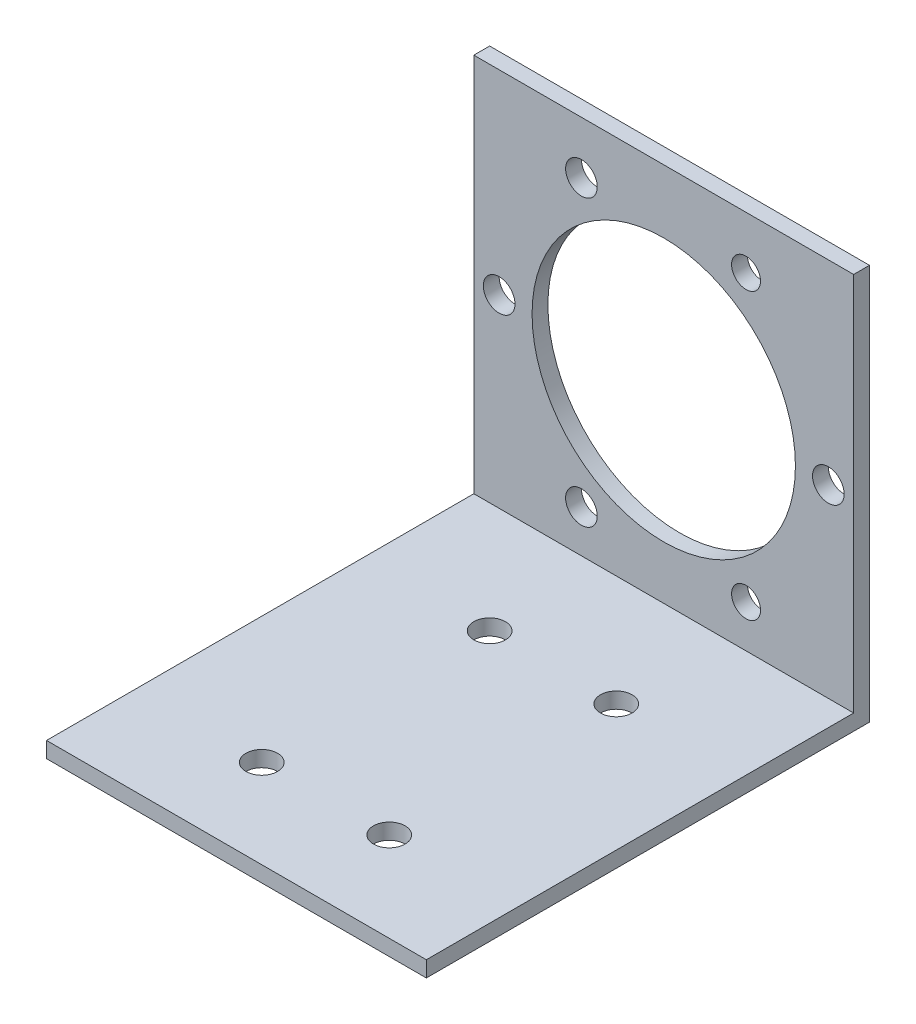
SolidWorks part; units mm, degrees
ref_plane "Front Plane" through (0, 0, 0) normal (0, 0, 1) x (1, 0, 0)
ref_plane "Top Plane" through (0, 0, 0) normal (0, 1, 0) x (1, 0, 0)
ref_plane "Right Plane" through (0, 0, 0) normal (1, 0, 0) x (0, 0, -1)
sketch "Sketch1" plane through (0, 0, 0) normal (0, 0, 1) x (1, 0, 0)
  line L1 (0, 0) -> (38.1, 0)
  line L2 (0, 0) -> (0, 1.5875)
  line L3 (0, 1.5875) -> (38.1, 1.5875)
  line L4 (38.1, 0) -> (38.1, 1.5875)
  dimension "D1" = 38.1
  dimension "D2" = 1.5875
extrude "Boss-Extrude1" add sketch "Sketch1" along normal blind 44.45
sketch "Sketch2" plane through (0, 1.5875, 0) normal (0, 1, 0) x (1, 0, 0)
  line L0 (12.7, -44.45) -> (12.7, 0) construction
  line L1 (38.1, -44.45) -> (0, -44.45) construction
  line L2 (38.1, 0) -> (0, 0) construction
  line L3 (25.4, 0) -> (25.4, -44.45) construction
  line L4 (38.1, -44.45) -> (38.1, 0) construction
  line L5 (0, 0) -> (38.1, 0)
  line L6 (0, 0) -> (0, -1.5875)
  line L7 (0, -1.5875) -> (38.1, -1.5875)
  line L8 (38.1, 0) -> (38.1, -1.5875)
  line L10 (0, -44.45) -> (0, 0) construction
  circle A0 centre (12.7, -12.7) radius 1.5875 construction
  circle A2 centre (12.7, -35.56) radius 1.5875 construction
  circle A3 centre (25.4, -35.4699) radius 1.5875 construction
  circle A5 centre (25.4, -12.7) radius 1.5875 construction
  dimension "D3" = 3.175
  dimension "D6" = 3.175
  dimension "D9" = 3.175
  dimension "D10" = 3.175
  dimension "D4" = 12.7
  dimension "D5" = 12.7
  dimension "D8" = 8.9801
  dimension "D11" = 8.89
  dimension "D12" = 1.5875
  dimension "D13" = 12.7
  dimension "D14" = 12.7
extrude "Boss-Extrude2" add sketch "Sketch2" along normal blind 38.1
sketch "Sketch3" plane through (0, 0, 0) normal (0, 0, -1) x (-1, 0, 0)
  line L0 (0, 0) -> (-38.1, 0) construction
  line L1 (-38.1, 20.1295) -> (0, 20.1295) construction
  line L2 (-38.1, 0) -> (-38.1, 39.6875) construction
  line L3 (0, 39.6875) -> (0, 0) construction
  line L4 (-19.05, 20.1295) -> (-11.3996, 33.3803) construction
  line L5 (-19.05, 20.1295) -> (-10.602, 5.4972) construction
  line L6 (-19.05, 20.1295) -> (-29.4645, 38.1679) construction
  line L7 (-19.05, 20.1295) -> (-30.7265, -0.0948) construction
  circle A0 centre (-19.05, 20.1295) radius 13.208
  point P6 (-10.795, 5.8314)
  point P11 (-19.05, 20.1295)
  point P14 (-2.54, 20.1295)
  point P15 (-10.795, 34.4276)
  point P16 (-35.56, 20.1295)
  point P17 (-27.305, 5.8314)
  point P20 (-27.305, 34.4276)
  dimension "D3" = 26.416
  dimension "D1" = 20.1295
  dimension "D2" = 19.05
  dimension "D4" = 60
  dimension "D5" = 60
  dimension "D6" = 16.51
  dimension "D7" = 16.51
  dimension "D8" = 16.51
  dimension "D9" = 16.51
  dimension "D10" = 60
  dimension "D11" = 60
  dimension "D12" = 16.51
  dimension "D13" = 16.51
extrude "Cut-Extrude1" cut sketch "Sketch3" against normal through all contours A0
hole_wizard "1/8 (0.125) Diameter Hole3" positions "Sketch13" profile "Sketch12" hole size "1/8" standard "ANSI Inch" end condition through all
sketch "Sketch13" plane through (0, 0, 0) normal (0, 0, -1) x (-1, 0, 0)
  point P0 (-35.56, 20.1295)
  point P3 (-10.795, 34.4276)
  point P6 (-2.54, 20.1295)
  point P9 (-10.795, 5.8314)
sketch "Sketch12" plane through (35.56, 20.1295, 0) normal (1, 0, 0) x (0, 1, 0)
  line L0 (0, 0) -> (0, 44.45)
  line L1 (0, 44.45) -> (1.5875, 44.45)
  line L2 (1.5875, 44.45) -> (1.5875, 0)
  line L5 (1.5875, 0) -> (0, 0)
  line L11 (0, -6.35) -> (0, 107.95) construction
  dimension "Thru Hole Dia." = 3.175
  dimension "Thru Hole Depth" = 44.45
hole_wizard "1/8 (0.125) Diameter Hole4" positions "Sketch14" profile "Sketch15" hole size "1/8" standard "ANSI Inch" end condition through all
sketch "Sketch14" plane through (0, 1.5875, 0) normal (0, 1, 0) x (1, 0, 0)
  point P0 (25.4, -12.7)
  point P3 (12.7, -12.7)
  point P6 (12.7, -35.56)
  point P9 (25.4, -35.4699)
sketch "Sketch15" plane through (25.4, 1.5875, 12.7) normal (1, 0, 0) x (0, 0, 1)
  line L0 (0, 0) -> (0, 1.5875)
  line L1 (0, 1.5875) -> (1.5875, 1.5875)
  line L2 (1.5875, 1.5875) -> (1.5875, 0)
  line L5 (1.5875, 0) -> (0, 0)
  line L11 (0, -6.35) -> (0, 107.95) construction
  dimension "Thru Hole Dia." = 3.175
  dimension "Thru Hole Depth" = 1.5875
hole_wizard "Ø2.9 (2.9) Diameter Hole1" positions "Sketch16" profile "Sketch17" hole size "Ø2.9" standard "ANSI Metric"
sketch "Sketch16" plane through (0, 0, 0) normal (0, 0, -1) x (-1, 0, 0)
  point P0 (-27.305, 5.8314)
  point P3 (-27.305, 34.4276)
sketch "Sketch17" plane through (27.305, 5.8314, 0) normal (1, 0, 0) x (0, 1, 0)
  line L0 (0, 0) -> (0, 4.4272)
  line L1 (0, 4.4272) -> (1.45, 3.556)
  line L2 (1.45, 3.556) -> (1.45, 0)
  line L5 (1.45, 0) -> (0, 0)
  line L10 (0, 4.4272) -> (-1.45, 3.556) construction
  line L11 (0, -6.35) -> (0, 107.95) construction
  dimension "Hole Dia." = 2.9
  dimension "Hole Depth" = 3.556
  dimension "Drill Angle" = 118
